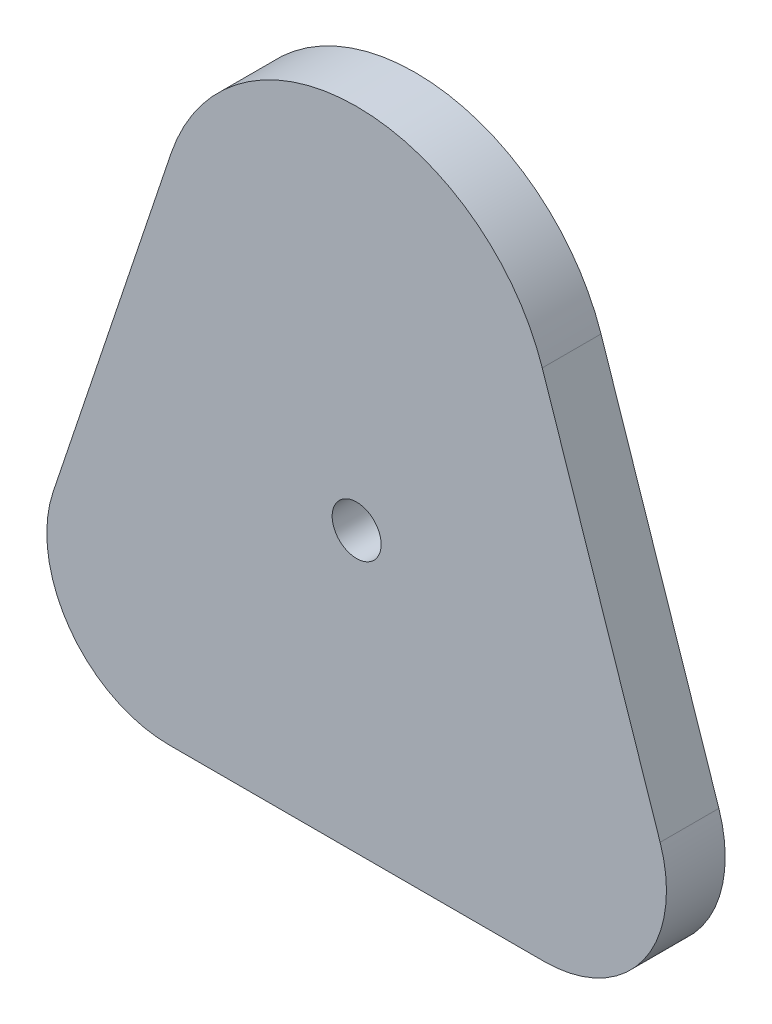
SolidWorks part; units mm, degrees
ref_plane "Спереди" through (0, 0, 0) normal (0, 0, 1) x (1, 0, 0)
ref_plane "Сверху" through (0, 0, 0) normal (0, 1, 0) x (1, 0, 0)
ref_plane "Справа" through (0, 0, 0) normal (1, 0, 0) x (0, 0, -1)
other "Configuration Table"
sketch "Эскиз1" plane through (0, 0, 0) normal (0, 0, 1) x (1, 0, 0)
  line L0 (0, 0) -> (0, 25) construction
  line L1 (-78.1858, 0) -> (67.4428, 0) construction
  line L2 (0, 0) -> (-19.1511, -16.0697) construction
  line L3 (0, 0) -> (19.1511, -16.0697) construction
  line L4 (-18.9649, 23.8509) -> (-31.0041, -12.1004)
  line L5 (18.9649, 23.8509) -> (31.0041, -12.1004)
  line L6 (19.1511, -28.5697) -> (-19.1511, -28.5697)
  line L7 (-19.1511, -16.0697) -> (-29.5693, -24.8116)
  circle A0 centre (0, 0) radius 38.6 construction
  circle A1 centre (0, 17.5) radius 20
  circle A2 centre (-19.1511, -16.0697) radius 12.5
  circle A3 centre (19.1511, -16.0697) radius 12.5
  point P10 (0, 0)
  point P19 (0, 37.5)
  point P20 (0, 38.6)
  point P21 (0, 0)
  point P22 (-28.7267, -24.1045)
  point P23 (0, 0)
  dimension "D1" = 77.2
  dimension "D2" = 40
  dimension "D5" = 25
  dimension "D6" = 25
  dimension "D3" = 17.5
  dimension "D7" = 25
  dimension "D4" = 40
  dimension "D8" = 40
  dimension "D9" = 25
  dimension "D10" = 1.1
  dimension "D12" = 40
  dimension "D11" = 1.1
extrude "Бобышка-Вытянуть1" add sketch "Эскиз1" along normal blind 6
sketch "Эскиз3" plane through (0, 0, 6) normal (0, 0, 1) x (1, 0, 0)
  circle A0 centre (0, 0) radius 2.5
  dimension "D1" = 5
extrude "Вырез-Вытянуть1" cut sketch "Эскиз3" against normal through all
equation "\"D12@Эскиз1\"=\"D4@Эскиз1\""
